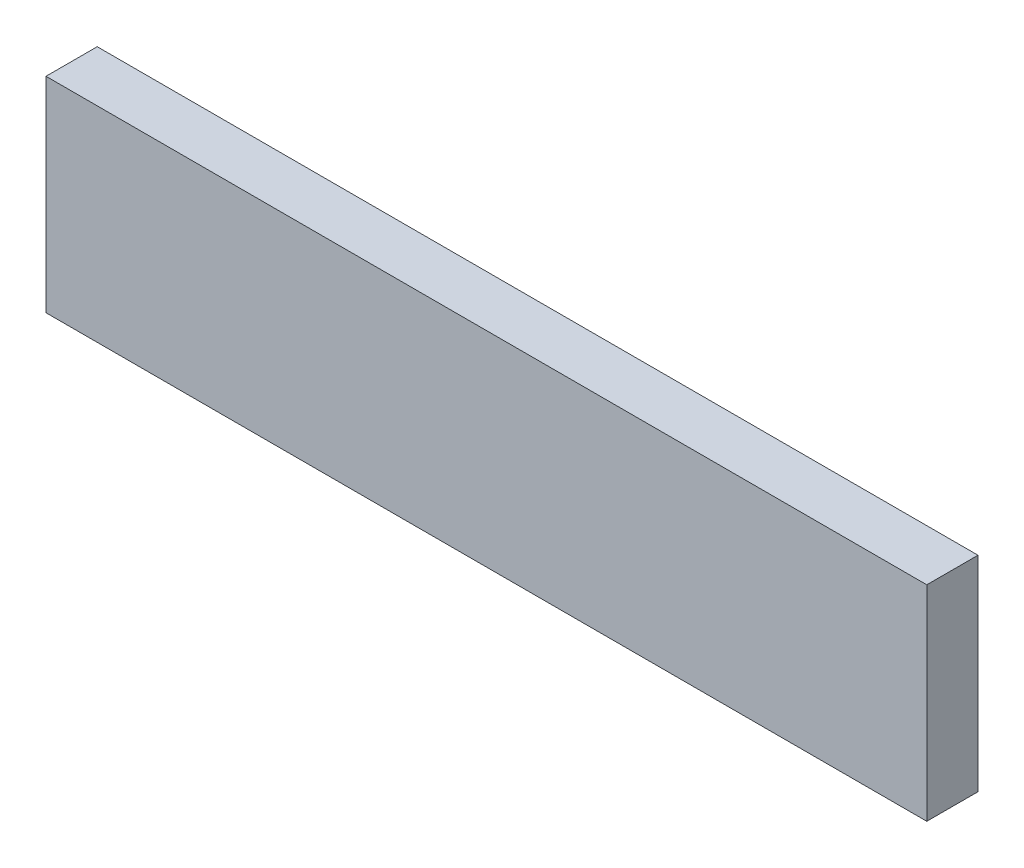
SolidWorks part; units mm, degrees
ref_plane "Plan de face" through (0, 0, 0) normal (0, 0, 1) x (1, 0, 0)
ref_plane "Plan de dessus" through (0, 0, 0) normal (0, 1, 0) x (1, 0, 0)
ref_plane "Plan de droite" through (0, 0, 0) normal (1, 0, 0) x (0, 0, -1)
sketch "Esquisse1" plane through (0, 0, 0) normal (0, 0, 1) x (1, 0, 0)
  line L1 (-50.6256, 20) -> (35.3744, 20)
  line L2 (-50.6256, 20) -> (-50.6256, 0)
  line L3 (-50.6256, 0) -> (35.3744, 0)
  line L4 (35.3744, 20) -> (35.3744, 0)
  point P6 (37.1931, 0.1299)
  dimension "D1" = 86
  dimension "D2" = 20
extrude "Boss.-Extru.1" add sketch "Esquisse1" along normal blind 5
